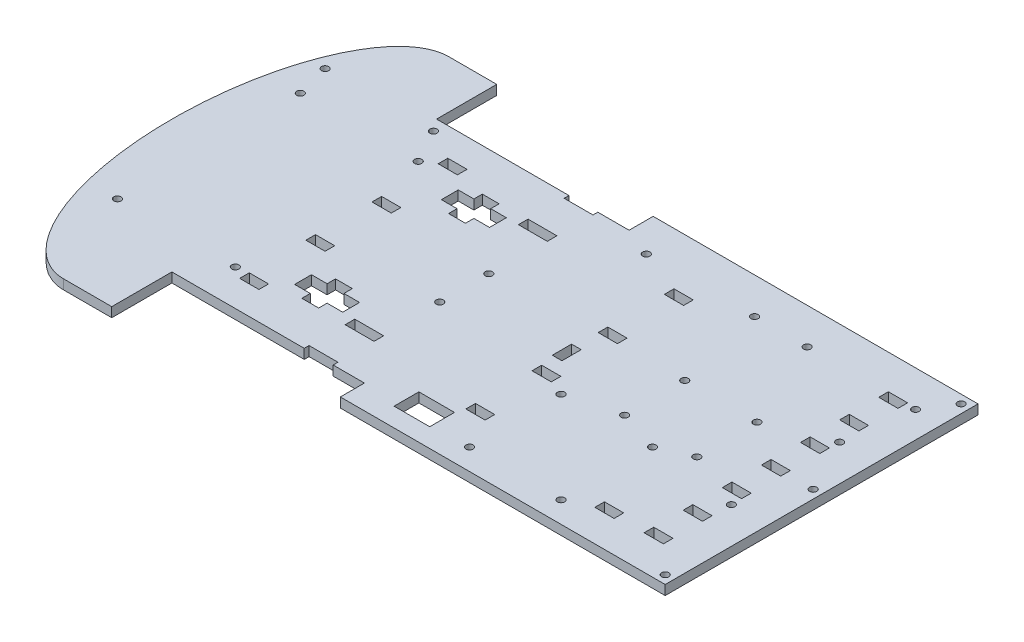
SolidWorks part; units mm, degrees
ref_plane "Front Plane" through (0, 0, 0) normal (0, 0, 1) x (1, 0, 0)
ref_plane "Top Plane" through (0, 0, 0) normal (0, 1, 0) x (1, 0, 0)
ref_plane "Right Plane" through (0, 0, 0) normal (1, 0, 0) x (0, 0, -1)
sketch "Sketch1" plane through (0, 0, 0) normal (0, 1, 0) x (1, 0, 0)
  line L0 (-70, -55) -> (-145, -55)
  line L1 (-65, 65) -> (70, 65)
  line L3 (-65, -65) -> (70, -65)
  line L4 (70, 65) -> (70, -65)
  line L5 (-65, 60.3571) -> (70, -65) construction
  line L6 (-65, -60.3571) -> (70, 65) construction
  line L7 (-70, 55) -> (-65, 55)
  line L8 (-145, 55) -> (-70, 55)
  line L9 (-145, -55) -> (-145, -80)
  line L10 (-145, 55) -> (-145, 80)
  line L12 (-145, 80) -> (-165, 80)
  line L13 (-65, 55) -> (-65, 65)
  line L14 (-165, -80) -> (-145, -80)
  line L15 (-70, -55) -> (-65, -55)
  line L16 (-65, -55) -> (-65, -65)
  ellipse E0 centre (-165, 0) end of major axis (-165, 80) minor radius 35 (-165, 80) -> (-165, -80) ccw
  point P0 (0, 0)
  dimension "D1" = 130
  dimension "D3" = 10
  dimension "D4" = 10
  dimension "D5" = 75
  dimension "D6" = 25
  dimension "D7" = 25
  dimension "D8" = 5
  dimension "D9" = 160
  dimension "D10" = 70
  dimension "D11" = 5
extrude "Boss-Extrude1" add sketch "Sketch1" along normal blind 4
sketch "Sketch3" plane through (-6.9856, 4, -5.2116) normal (0, 1, 0) x (1, 0, 0)
  line L0 (-175.6169, -45.25) -> (-175.6169, 30.75) construction
  line L2 (-126.6169, -45.25) -> (-126.6169, 30.75) construction
  line L3 (-126.6169, -45.25) -> (-175.6169, -45.25) construction
  line L4 (-175.6169, 30.75) -> (-126.6169, 30.75) construction
  line L5 (-151.1169, -45.25) -> (-151.1169, 30.75) construction
  line L6 (-175.6169, -7.25) -> (-126.6169, -7.25) construction
  circle A0 centre (-175.6169, 30.75) radius 1.5
  circle A4 centre (-126.6169, -45.25) radius 1.5
  circle A5 centre (-175.6169, -45.25) radius 1.5
  circle A6 centre (-126.6169, 30.75) radius 1.5
  dimension "D1" = 3
  dimension "D2" = 3
  dimension "D3" = 76
  dimension "D4" = 49
extrude "Cut-Extrude1" cut sketch "Sketch3" against normal through all
sketch "Sketch4" plane through (0, 4, 0) normal (0, 1, 0) x (1, 0, 0)
  line L0 (-124.591, 55) -> (-124.591, -55) construction
  line L1 (-65, 55) -> (-145, 55) construction
  line L2 (-145, -55) -> (-65, -55) construction
  line L3 (-200, 0) -> (70, 0) construction
  line L4 (70, -65) -> (70, 65) construction
  line L5 (-128.591, 15.75) -> (-120.591, 15.75)
  line L6 (-128.591, 43.25) -> (-120.591, 43.25)
  line L7 (-128.591, 43.25) -> (-128.591, 39.25)
  line L8 (-128.591, 39.25) -> (-120.591, 39.25)
  line L9 (-120.591, 43.25) -> (-120.591, 39.25)
  line L10 (-128.591, 43.25) -> (-120.591, 39.25) construction
  line L11 (-128.591, 39.25) -> (-120.591, 43.25) construction
  line L12 (-128.591, 15.75) -> (-128.591, 11.75)
  line L13 (-124.591, 27.5) -> (-124.591, -82.5) construction
  line L14 (-128.591, 11.75) -> (-120.591, 11.75)
  line L15 (-120.591, 15.75) -> (-120.591, 11.75)
  line L16 (-128.591, -11.75) -> (-120.591, -11.75)
  line L17 (-128.591, -11.75) -> (-128.591, -15.75)
  line L18 (-124.591, 0) -> (-124.591, -110) construction
  line L19 (-128.591, -15.75) -> (-120.591, -15.75)
  line L20 (-120.591, -11.75) -> (-120.591, -15.75)
  line L21 (-128.591, -39.25) -> (-120.591, -39.25)
  line L22 (-128.591, -39.25) -> (-128.591, -43.25)
  line L23 (-124.591, -27.5) -> (-124.591, -137.5) construction
  line L24 (-128.591, -43.25) -> (-120.591, -43.25)
  line L25 (-120.591, -39.25) -> (-120.591, -43.25)
  line L26 (-34.591, 43.25) -> (-26.591, 43.25)
  line L27 (-34.591, 39.25) -> (-26.591, 39.25)
  line L28 (-34.591, 43.25) -> (-34.591, 39.25)
  line L29 (-26.591, 43.25) -> (-26.591, 39.25)
  line L30 (-34.591, 15.75) -> (-26.591, 15.75)
  line L31 (-26.591, 15.75) -> (-26.591, 11.75)
  line L32 (-34.591, 11.75) -> (-26.591, 11.75)
  line L33 (-34.591, 15.75) -> (-34.591, 11.75)
  line L34 (-34.591, -11.75) -> (-26.591, -11.75)
  line L35 (-26.591, -11.75) -> (-26.591, -15.75)
  line L36 (-34.591, -15.75) -> (-26.591, -15.75)
  line L37 (-34.591, -11.75) -> (-34.591, -15.75)
  line L38 (-34.591, -39.25) -> (-26.591, -39.25)
  line L39 (-26.591, -39.25) -> (-26.591, -43.25)
  line L40 (-34.591, -43.25) -> (-26.591, -43.25)
  line L41 (-34.591, -39.25) -> (-34.591, -43.25)
  ellipse E0 centre (-165, 0) end of major axis (-165, -80) minor radius 35 (-165, 80) -> (-165, -80) ccw construction
  point P17 (-124.591, 41.25)
  dimension "D1" = 8
  dimension "D2" = 4
  dimension "D3" = 13.75
  dimension "D4" = 4
  dimension "D5" = 2
extrude "Cut-Extrude2" cut sketch "Sketch4" against normal through all
sketch "Sketch12" plane through (0, 4, 0) normal (0, 1, 0) x (1, 0, 0)
  line L0 (-65, 55) -> (-145, 55) construction
  line L1 (-90, 55) -> (-78, 55)
  line L2 (-90, 55) -> (-90, 53)
  line L3 (-90, 53) -> (-78, 53)
  line L4 (-78, 55) -> (-78, 53)
  line L5 (-65, 65) -> (-65, 55) construction
  line L6 (-200, 0) -> (70, 0) construction
  line L7 (70, -65) -> (70, 65) construction
  line L8 (-78, -55) -> (-78, -53)
  line L9 (-90, -53) -> (-78, -53)
  line L10 (-90, -55) -> (-90, -53)
  line L11 (-90, -55) -> (-78, -55)
  line L13 (-90, -34) -> (-78, -34)
  line L14 (-90, -34) -> (-90, -38)
  line L15 (-90, -38) -> (-78, -38)
  line L16 (-78, -34) -> (-78, -38)
  line L17 (-115, -27) -> (-108.5, -27)
  line L18 (-115, -27) -> (-115, -34)
  line L19 (-115, -34) -> (-108.5, -34)
  line L20 (-95, -27) -> (-95, -34)
  line L21 (-101.5, -27) -> (-95, -27)
  line L22 (-101.5, -23.5) -> (-108.5, -23.5)
  line L23 (-101.5, -23.5) -> (-101.5, -27)
  line L25 (-108.5, -23.5) -> (-108.5, -27)
  line L32 (-101.5, -34) -> (-95, -34)
  line L40 (-78, 34) -> (-78, 38)
  line L41 (-90, 38) -> (-78, 38)
  line L42 (-90, 34) -> (-90, 38)
  line L43 (-90, 34) -> (-78, 34)
  line L44 (-108.5, -34) -> (-108.5, -37.5)
  line L45 (-108.5, -37.5) -> (-101.5, -37.5)
  line L46 (-101.5, -37.5) -> (-101.5, -34)
  line L47 (-101.5, 37.5) -> (-101.5, 34)
  line L48 (-108.5, 37.5) -> (-101.5, 37.5)
  line L49 (-108.5, 34) -> (-108.5, 37.5)
  line L50 (-101.5, 34) -> (-95, 34)
  line L51 (-108.5, 23.5) -> (-108.5, 27)
  line L52 (-101.5, 23.5) -> (-101.5, 27)
  line L53 (-101.5, 23.5) -> (-108.5, 23.5)
  line L54 (-101.5, 27) -> (-95, 27)
  line L55 (-95, 27) -> (-95, 34)
  line L56 (-115, 34) -> (-108.5, 34)
  line L57 (-115, 27) -> (-115, 34)
  line L58 (-115, 27) -> (-108.5, 27)
  ellipse E0 centre (-165, 0) end of major axis (-165, -80) minor radius 35 (-165, 80) -> (-165, -80) ccw construction
  point P33 (-105, -30.5)
  point P51 (-105, 30.5)
  dimension "D1" = 13
  dimension "D2" = 2
  dimension "D4" = 3.5
  dimension "D5" = 4
  dimension "D6" = 12
  dimension "D7" = 20
  dimension "D8" = 7
  dimension "D9" = 5
  dimension "D10" = 7
  dimension "D11" = 6.5
  dimension "D12" = 6.5
  dimension "D13" = 3.5
extrude "Cut-Extrude8" cut sketch "Sketch12" against normal through all
sketch "Sketch5" plane through (0, 4, 0) normal (0, 1, 0) x (1, 0, 0)
  line L1 (-41.25, 20.4) -> (-41.25, -20.4) construction
  line L2 (-41.25, 20.4) -> (-115.8417, 20.4) construction
  line L3 (-115.8417, 20.4) -> (-115.75, -20.4) construction
  line L4 (-41.25, -20.4) -> (-115.75, -20.4) construction
  line L5 (-41.25, 20.4) -> (-115.75, -20.4) construction
  line L8 (-41.25, 0) -> (-115.7958, 0) construction
  line L11 (-31.9724, 2.0658) -> (-31.9724, -5.9342)
  line L12 (-31.9724, 2.0658) -> (-35.9724, 2.0658)
  line L13 (-35.9724, 2.0658) -> (-35.9724, -5.9342)
  line L14 (-31.9724, -5.9342) -> (-35.9724, -5.9342)
  line L15 (-31.9724, 2.0658) -> (-35.9724, -5.9342) construction
  line L16 (-35.9724, 2.0658) -> (-31.9724, -5.9342) construction
  circle A0 centre (-78.5, 10.2) radius 1.5
  circle A1 centre (-78.5, -10.2) radius 1.5
  point P0 (-78.5, 0)
  point P24 (-33.9724, -1.9342)
  dimension "D5" = 3
  dimension "D6" = 4
  dimension "D7" = 8
extrude "Cut-Extrude3" cut sketch "Sketch5" against normal through all
sketch "Sketch7" plane through (0, 4, 0) normal (0, 1, 0) x (1, 0, 0)
  line L0 (70, 65) -> (-65, 65) construction
  line L1 (-50.5112, 57.15) -> (-35.7112, 57.15) construction
  line L2 (-50.5112, 57.15) -> (-50.5112, 46.85) construction
  line L3 (-50.5112, 46.85) -> (-35.7112, 46.85) construction
  line L4 (-35.7112, 57.15) -> (-35.7112, 46.85) construction
  line L5 (-50.5112, 57.15) -> (-35.7112, 46.85) construction
  line L6 (-50.5112, 46.85) -> (-35.7112, 57.15) construction
  line L7 (-200, 0) -> (70, 0) construction
  line L8 (70, -65) -> (70, 65) construction
  line L9 (-50.5112, -46.85) -> (-35.7112, -57.15) construction
  line L10 (-50.5112, -57.15) -> (-35.7112, -46.85) construction
  line L11 (-35.7112, -57.15) -> (-35.7112, -46.85)
  line L12 (-50.5112, -46.85) -> (-35.7112, -46.85)
  line L13 (-50.5112, -57.15) -> (-50.5112, -46.85)
  line L14 (-50.5112, -57.15) -> (-35.7112, -57.15)
  ellipse E0 centre (-165, 0) end of major axis (-165, -80) minor radius 35 (-165, 80) -> (-165, -80) ccw construction
  point P0 (-43.1112, 52)
  point P22 (-43.1112, -52)
  dimension "D1" = 14.8
  dimension "D2" = 10.3
  dimension "D3" = 13
extrude "Cut-Extrude4" cut sketch "Sketch7" against normal through all
sketch "Sketch8" plane through (-25.4276, 4, 2.119) normal (0, 1, 0) x (1, 0, 0)
  circle A0 centre (5.31, -16.0521) radius 1.5
  circle A1 centre (43.31, -16.0521) radius 1.5
  circle A2 centre (43.31, -54.0521) radius 1.5
  circle A3 centre (5.31, -54.0521) radius 1.5
  point P0 (5.31, -54.0521)
  point P1 (43.31, -54.0521)
  point P2 (43.31, -16.0521)
  point P3 (5.31, -16.0521)
  dimension "D1" = 3
  dimension "D2" = 3
  dimension "D3" = 3
  dimension "D4" = 3
  dimension "D5" = 38
  dimension "D6" = 38
  dimension "D7" = 38
extrude "Cut-Extrude5" cut sketch "Sketch8" against normal through all
sketch "Sketch9" plane through (0, 4, 0) normal (0, 1, 0) x (1, 0, 0)
  line L0 (51, 65) -> (51, -65) construction
  line L1 (70, 65) -> (-65, 65) construction
  line L2 (-65, -65) -> (70, -65) construction
  line L3 (-200, 0) -> (70, 0) construction
  line L4 (70, -65) -> (70, 65) construction
  line L5 (47, -14.25) -> (55, -14.25)
  line L6 (47, 2) -> (55, 2)
  line L7 (47, 2) -> (47, -2)
  line L8 (47, -2) -> (55, -2)
  line L9 (55, 2) -> (55, -2)
  line L10 (47, 2) -> (55, -2) construction
  line L11 (47, -2) -> (55, 2) construction
  line L12 (47, -14.25) -> (47, -18.25)
  line L13 (47, -18.25) -> (55, -18.25)
  line L14 (55, -14.25) -> (55, -18.25)
  line L15 (47, -30.5) -> (55, -30.5)
  line L16 (47, -30.5) -> (47, -34.5)
  line L17 (47, -34.5) -> (55, -34.5)
  line L18 (55, -30.5) -> (55, -34.5)
  line L19 (47, -46.75) -> (55, -46.75)
  line L20 (47, -46.75) -> (47, -50.75)
  line L21 (47, -50.75) -> (55, -50.75)
  line L22 (55, -46.75) -> (55, -50.75)
  line L23 (55, 46.75) -> (55, 50.75)
  line L24 (47, 50.75) -> (55, 50.75)
  line L25 (47, 46.75) -> (47, 50.75)
  line L26 (47, 46.75) -> (55, 46.75)
  line L27 (55, 30.5) -> (55, 34.5)
  line L28 (47, 34.5) -> (55, 34.5)
  line L29 (47, 30.5) -> (47, 34.5)
  line L30 (47, 30.5) -> (55, 30.5)
  line L31 (55, 14.25) -> (55, 18.25)
  line L32 (47, 18.25) -> (55, 18.25)
  line L33 (47, 14.25) -> (47, 18.25)
  line L34 (47, 14.25) -> (55, 14.25)
  ellipse E0 centre (-165, 0) end of major axis (-165, -80) minor radius 35 (-165, 80) -> (-165, -80) ccw construction
  point P17 (51, 0)
  dimension "D1" = 8
  dimension "D2" = 4
  dimension "D4" = 19
  dimension "D3" = 4
extrude "Cut-Extrude6" cut sketch "Sketch9" against normal through all
sketch "Sketch10" plane through (0, 4, 0) normal (0, 1, 0) x (1, 0, 0)
  line L0 (-200, 0) -> (70, 0) construction
  line L5 (70, -65) -> (70, 65) construction
  line L6 (70, 65) -> (-65, 65) construction
  line L11 (30.635, 12.5) -> (30.635, -12.5) construction
  line L12 (30.635, 12.5) -> (0.635, 12.5) construction
  line L13 (0.635, 12.5) -> (0.635, -12.5) construction
  line L14 (30.635, -12.5) -> (0.635, -12.5) construction
  line L15 (30.635, 12.5) -> (0.635, -12.5) construction
  line L16 (0.635, 12.5) -> (30.635, -12.5) construction
  line L21 (-12.014, 50) -> (34.986, 50) construction
  line L22 (-12.014, 50) -> (-12.014, 15) construction
  line L23 (-12.014, 15) -> (34.986, 15) construction
  line L24 (34.986, 50) -> (34.986, 15) construction
  circle A4 centre (30.635, 12.5) radius 1.5
  circle A5 centre (0.635, 12.5) radius 1.5
  circle A6 centre (30.635, -12.5) radius 1.5
  circle A7 centre (0.635, -12.5) radius 1.5
  ellipse E0 centre (-165, 0) end of major axis (-165, -80) minor radius 35 (-165, 80) -> (-165, -80) ccw construction
  point P11 (15.635, 0)
  dimension "D5" = 3
  dimension "D3" = 3
  dimension "D4" = 3
  dimension "D6" = 3
  dimension "D1" = 30
  dimension "D2" = 25
  dimension "D7" = 47
  dimension "D8" = 35
  dimension "D9" = 15
extrude "Cut-Extrude7" cut sketch "Sketch10" against normal through all
sketch "Sketch13" plane through (0, 4, 0) normal (0, 1, 0) x (1, 0, 0)
  line L0 (-200, 0) -> (70, 0) construction
  line L1 (27.616, 51.8491) -> (35.616, 51.8491) construction
  line L2 (27.616, 51.8491) -> (27.616, 47.8491) construction
  line L3 (27.616, 47.8491) -> (35.616, 47.8491) construction
  line L4 (35.616, 51.8491) -> (35.616, 47.8491) construction
  line L5 (70, -65) -> (70, 65) construction
  line L6 (35.616, -51.8491) -> (35.616, -47.8491)
  line L7 (27.616, -47.8491) -> (35.616, -47.8491)
  line L8 (27.616, -51.8491) -> (27.616, -47.8491)
  line L9 (27.616, -51.8491) -> (35.616, -51.8491)
  ellipse E0 centre (-165, 0) end of major axis (-165, -80) minor radius 35 (-165, 80) -> (-165, -80) ccw construction
  dimension "D1" = 8
  dimension "D2" = 4
extrude "Cut-Extrude9" cut sketch "Sketch13" against normal through all
sketch "Sketch14" plane through (0, 4, 0) normal (0, 1, 0) x (1, 0, 0)
  line L0 (-200, 0) -> (70, 0) construction
  line L1 (70, -65) -> (70, 65) construction
  line L2 (63, 65) -> (63, -65) construction
  line L3 (70, 65) -> (-65, 65) construction
  line L4 (-65, -65) -> (70, -65) construction
  line L5 (70, 58) -> (-189.1062, 58) construction
  line L6 (63, 65) -> (70, 58) construction
  circle A0 centre (66.5, 61.5) radius 1.5
  circle A1 centre (66.5, 0) radius 1.5
  circle A2 centre (66.5, -61.5) radius 1.5
  ellipse E0 centre (-165, 0) end of major axis (-165, -80) minor radius 35 (-165, 80) -> (-165, -80) ccw construction
  dimension "D3" = 3
  dimension "D4" = 3
  dimension "D1" = 7
  dimension "D2" = 7
extrude "Cut-Extrude10" cut sketch "Sketch14" against normal through all
sketch "Sketch15" plane through (0, 4, 0) normal (0, 1, 0) x (1, 0, 0)
  line L0 (70, 50) -> (-192.3219, 50) construction
  line L1 (70, -65) -> (70, 65) construction
  line L5 (-200, 0) -> (70, 0) construction
  line L6 (-200, -22.5) -> (70, -22.5) construction
  line L7 (-200, 22.5) -> (70, 22.5) construction
  circle A0 centre (59, 50) radius 1.5
  circle A1 centre (14, 50) radius 1.5
  circle A2 centre (-52.8487, 50) radius 1.5
  circle A3 centre (-7.8487, 50) radius 1.5
  circle A4 centre (-186.3219, 50) radius 1.5
  circle A5 centre (-141.3219, 50) radius 1.5
  circle A6 centre (55, 22.5) radius 1.5
  circle A7 centre (55, -22.5) radius 1.5
  ellipse E0 centre (-165, 0) end of major axis (-165, -80) minor radius 35 (-165, 80) -> (-165, -80) ccw construction
  dimension "D3" = 3
  dimension "D4" = 3
  dimension "D6" = 3
  dimension "D7" = 3
  dimension "D9" = 3
  dimension "D10" = 3
  dimension "D14" = 15
  dimension "D15" = 3
  dimension "D2" = 11
  dimension "45mm" = 45
  dimension "D5" = 45
  dimension "D8" = 45
  dimension "D11" = 6
  dimension "D12" = 22.5
  dimension "D16" = 15
  dimension "D13" = 22.5
extrude "Cut-Extrude11" cut sketch "Sketch15" against normal through all
